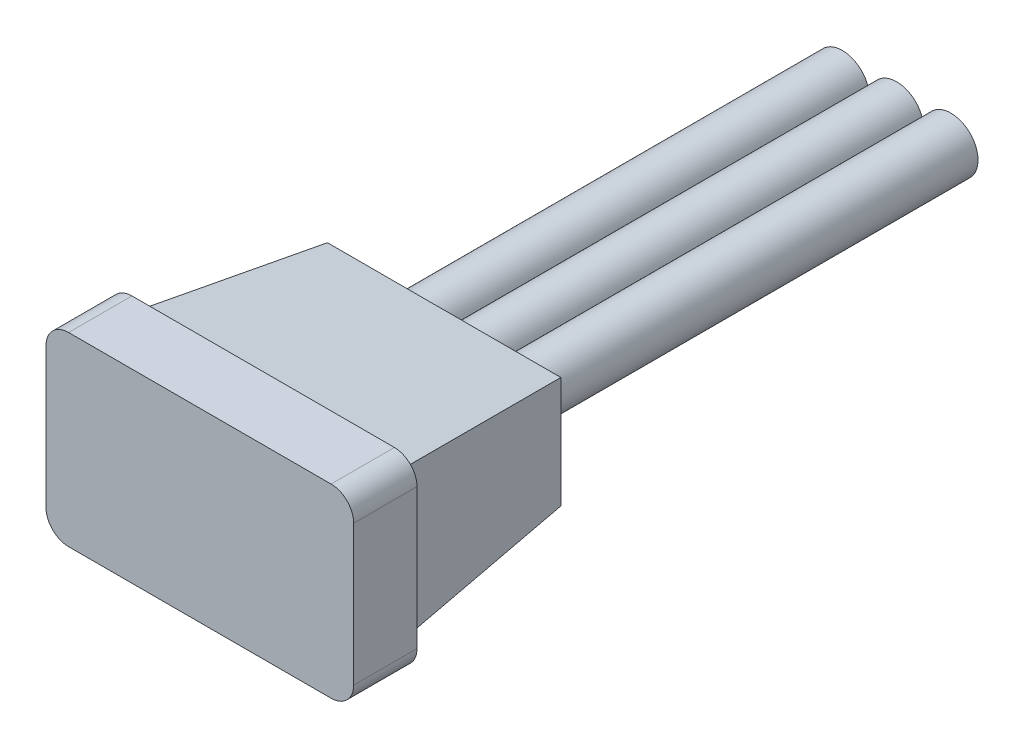
SolidWorks part; units mm, degrees
ref_plane "Front Plane" through (0, 0, 0) normal (0, 0, 1) x (1, 0, 0)
ref_plane "Top Plane" through (0, 0, 0) normal (0, 1, 0) x (1, 0, 0)
ref_plane "Right Plane" through (0, 0, 0) normal (1, 0, 0) x (0, 0, -1)
sketch "Sketch1" plane through (0, 0, 0) normal (0, 0, 1) x (1, 0, 0)
  line L1 (-3.4, 2.05) -> (3.4, 2.05)
  line L2 (-3.4, 2.05) -> (-3.4, -2.05)
  line L3 (-3.4, -2.05) -> (3.4, -2.05)
  line L4 (3.4, 2.05) -> (3.4, -2.05)
  line L5 (-3.4, 2.05) -> (3.4, -2.05) construction
  line L6 (-3.4, -2.05) -> (3.4, 2.05) construction
  point P0 (0, 0)
  dimension "D1" = 6.8
  dimension "D2" = 4.1
extrude "Boss-Extrude1" add sketch "Sketch1" against normal blind 1.4
sketch "Sketch2" plane through (0, 0, -1.4) normal (0, 0, -1) x (-1, 0, 0)
  line L1 (3, 1.65) -> (-3, 1.65)
  line L2 (3, 1.65) -> (3, -1.65)
  line L3 (3, -1.65) -> (-3, -1.65)
  line L4 (-3, 1.65) -> (-3, -1.65)
  line L5 (3, 1.65) -> (-3, -1.65) construction
  line L6 (3, -1.65) -> (-3, 1.65) construction
  line L7 (-3.4, 2.05) -> (3.4, 2.05) construction
  line L8 (-3.4, -2.05) -> (-3.4, 2.05) construction
  point P0 (0, 0)
  dimension "D1" = 0.4
  dimension "D2" = 0.4
extrude "Boss-Extrude2" add sketch "Sketch2" along normal blind 4 draft 6
fillet "Fillet1" radius 0.5 4 edges at (-3.4, -2.05, -0.7) (-3.4, 2.05, -0.7) (3.4, -2.05, -0.7) (3.4, 2.05, -0.7)
sketch "Sketch3" plane through (0, 0, -5.4) normal (0, 0, -1) x (-1, 0, 0)
  circle A0 centre (0, 0) radius 0.6
  dimension "D1" = 1.2
extrude "POSITIVE" add sketch "Sketch3" along normal blind 10 separate body
sketch "Sketch4" plane through (0, 0, -5.4) normal (0, 0, -1) x (-1, 0, 0)
  line L0 (1.2, 0) -> (0, 0) construction
  circle A0 centre (1.2, 0) radius 0.6
  circle A1 centre (0, 0) radius 0.6 construction
extrude "SIGNAL" add sketch "Sketch4" along normal up to surface (10 mm away) separate body up to face at (-0.6, 0, -15.4)
sketch "Sketch5" plane through (0, 0, -5.4) normal (0, 0, -1) x (-1, 0, 0)
  line L0 (0, 0) -> (-1.2, 0) construction
  circle A0 centre (-1.2, 0) radius 0.6
  circle A1 centre (0, 0) radius 0.6 construction
extrude "NEGATIVE" add sketch "Sketch5" along normal up to surface (10 mm away) separate body up to face at (-0.6, 0, -15.4)
